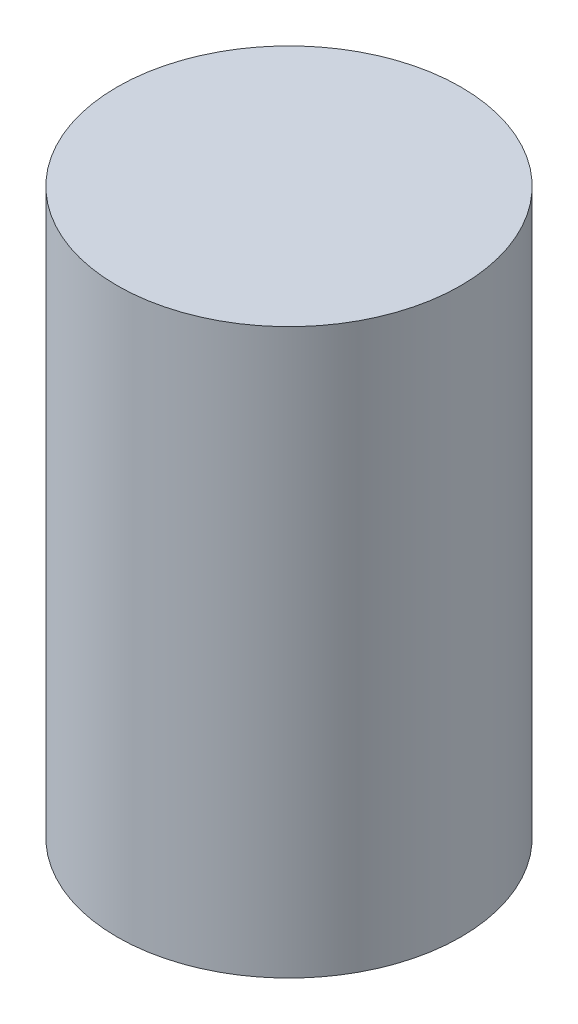
SolidWorks part; units mm, degrees
ref_plane "Front Plane" through (0, 0, 0) normal (0, 0, 1) x (1, 0, 0)
ref_plane "Top Plane" through (0, 0, 0) normal (0, 1, 0) x (1, 0, 0)
ref_plane "Right Plane" through (0, 0, 0) normal (1, 0, 0) x (0, 0, -1)
sketch "Sketch2" plane through (0, 0, 0) normal (0, 1, 0) x (1, 0, 0)
  circle A0 centre (0, 0) radius 76.2
  dimension "D1" = 152.4
extrude "Boss-Extrude1" add sketch "Sketch2" along normal blind 250
